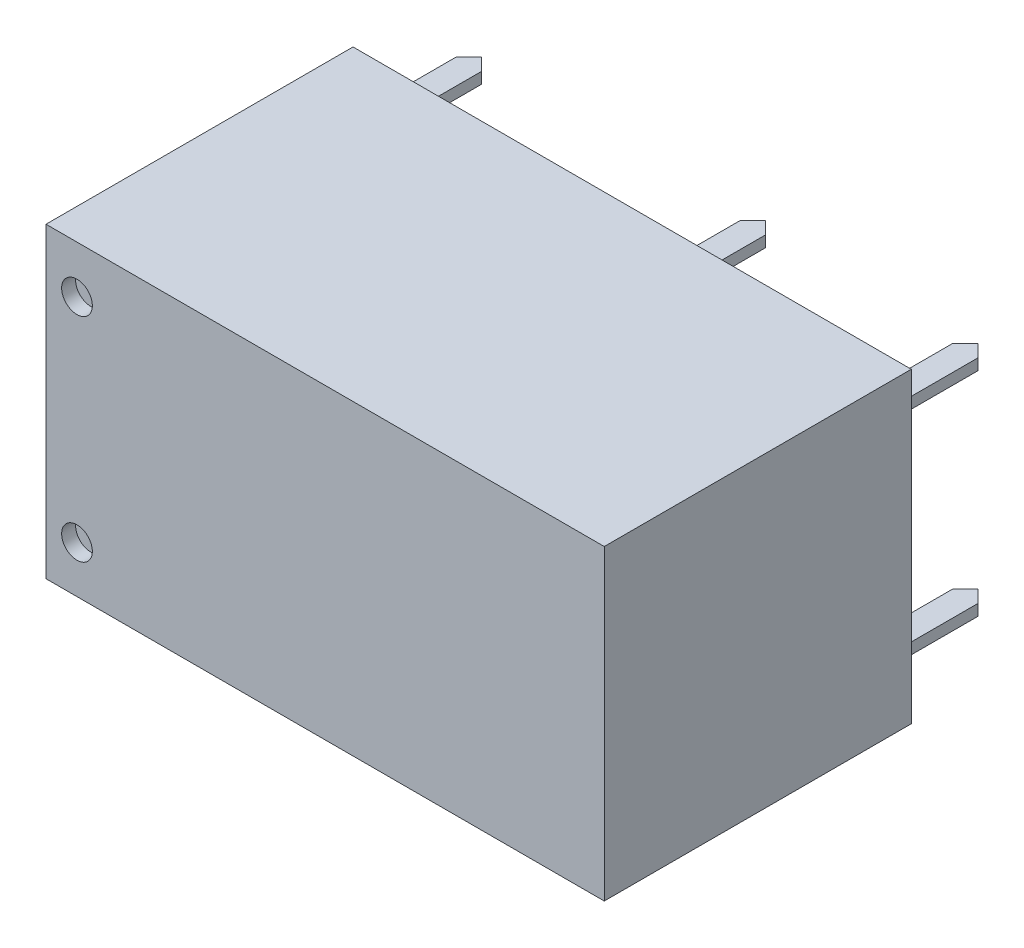
SolidWorks part; units mm, degrees
ref_plane "Ebene vorne" through (0, 0, 0) normal (0, 0, 1) x (1, 0, 0)
ref_plane "Ebene oben" through (0, 0, 0) normal (0, 1, 0) x (1, 0, 0)
ref_plane "Ebene rechts" through (0, 0, 0) normal (1, 0, 0) x (0, 0, -1)
sketch "Skizze1" plane through (0, 0, 0) normal (0, 0, 1) x (1, 0, 0)
  line L1 (-1.11, -9.3) -> (18.89, -9.3)
  line L2 (-1.11, -9.3) -> (-1.11, 1.7)
  line L3 (-1.11, 1.7) -> (18.89, 1.7)
  line L4 (18.89, -9.3) -> (18.89, 1.7)
  dimension "D1" = 20
  dimension "D2" = 11
  dimension "D3" = 1.11
  dimension "D4" = 1.7
extrude "Aufsatz-Linear austragen1" add sketch "Skizze1" along normal blind 11
sketch "Skizze2" plane through (0, 0, 11) normal (0, 0, 1) x (1, 0, 0)
  circle A0 centre (0, 0) radius 0.55
  circle A1 centre (0, -7.62) radius 0.55
  point P4 (0, 0)
  point P5 (0, 0)
  dimension "D1" = 1.1
  dimension "D2" = 7.62
extrude "Schnitt-Linear austragen1" cut sketch "Skizze2" against normal blind 0.5
sketch "Skizze3" plane through (0, 0, 0) normal (0, 1, 0) x (1, 0, 0)
  line L0 (-0.45, 0) -> (-0.45, 3.05)
  line L1 (-0.45, 3.05) -> (0, 3.5)
  line L2 (0, 3.5) -> (0.45, 3.05)
  line L3 (0.45, 3.05) -> (0.45, 0)
  line L4 (0.45, 0) -> (-0.45, 0)
  point P2 (0, 0)
  point P6 (-0.45, 1.525)
  dimension "D1" = 0.9
  dimension "D2" = 3.5
  dimension "D3" = 0.45
  dimension "D4" = 135
extrude "Aufsatz-Linear austragen2" add sketch "Skizze3" along normal blind 0.2 and the other way blind 0.2
pattern_linear "Lineares Muster1" count 2 spacing 10.16 along (1, 0, 0) of "Aufsatz-Linear austragen2"
pattern_linear "Lineares Muster2" count 2 spacing 17.78 along (1, 0, 0) of "Aufsatz-Linear austragen2"
pattern_linear "Lineares Muster3" count 2 spacing 7.62 along (0, -1, 0) of "Aufsatz-Linear austragen2", "Lineares Muster1", "Lineares Muster2"
